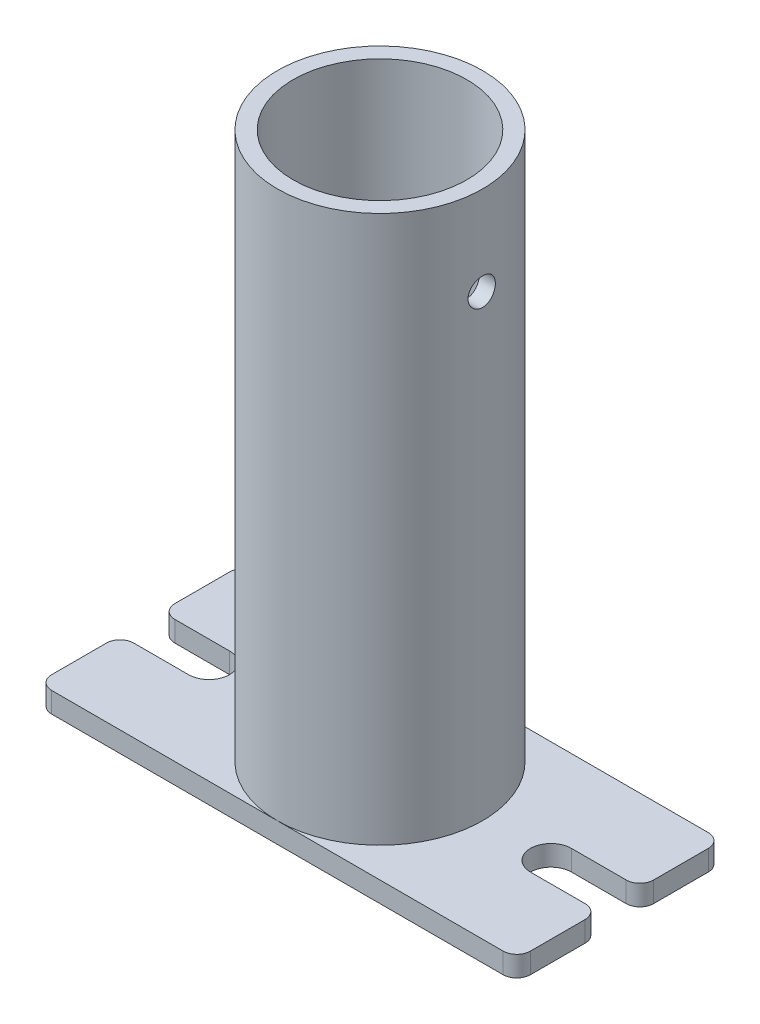
SolidWorks part; units mm, degrees
ref_plane "Front Plane" through (0, 0, 0) normal (0, 0, 1) x (1, 0, 0)
ref_plane "Top Plane" through (0, 0, 0) normal (0, 1, 0) x (1, 0, 0)
ref_plane "Right Plane" through (0, 0, 0) normal (1, 0, 0) x (0, 0, -1)
sketch "Sketch1" plane through (0, 0, 0) normal (0, 1, 0) x (1, 0, 0)
  line L0 (0, 15) -> (10, 15) construction
  line L1 (2, 0) -> (68, 0)
  line L2 (0, 2) -> (0, 10)
  line L3 (2, 30) -> (68, 30)
  line L4 (70, 2) -> (70, 10)
  line L5 (2, 18) -> (10, 18)
  line L6 (2, 12) -> (10, 12)
  line L7 (0, 20) -> (0, 28)
  line L8 (70, 15) -> (60, 15) construction
  line L9 (68, 12) -> (60, 12)
  line L10 (68, 18) -> (60, 18)
  line L11 (70, 20) -> (70, 28)
  arc A1 (10, 12) -> (10, 18) centre (10, 15) ccw
  arc A3 (60, 18) -> (60, 12) centre (60, 15) ccw
  arc A4 (68, 30) -> (70, 28) centre (68, 28) cw
  arc A5 (68, 18) -> (70, 20) centre (68, 20) ccw
  arc A6 (68, 12) -> (70, 10) centre (68, 10) cw
  arc A7 (68, 0) -> (70, 2) centre (68, 2) ccw
  arc A8 (2, 0) -> (0, 2) centre (2, 2) cw
  arc A9 (2, 12) -> (0, 10) centre (2, 10) ccw
  arc A10 (2, 18) -> (0, 20) centre (2, 20) cw
  arc A11 (0, 28) -> (2, 30) centre (2, 28) cw
  point P7 (5, 15)
  point P14 (65, 15)
  point P21 (70, 30)
  point P30 (0, 0)
  point P37 (0, 30)
  dimension "D3" = 2
  dimension "D1" = 30
  dimension "D2" = 70
extrude "Boss-Extrude2" add sketch "Sketch1" along normal blind 3
sketch "Sketch3" plane through (0, 3, 0) normal (0, 1, 0) x (1, 0, 0)
  line L0 (0, 10) -> (0, 2) construction
  circle A0 centre (35, 15) radius 15
  dimension "D1" = 35
extrude "Boss-Extrude3" add sketch "Sketch3" along normal blind 5
sketch "Sketch4" plane through (0, 8, 0) normal (0, 1, 0) x (1, 0, 0)
  circle A0 centre (35, 15) radius 12.7
  arc A1 (35, 0) -> (35, 30) centre (35, 15) ccw construction
  circle A2 centre (35, 15) radius 15
  dimension "D1" = 0
extrude "Boss-Extrude5" add sketch "Sketch4" along normal blind 75
sketch "Sketch5" plane through (70, 0, 0) normal (1, 0, 0) x (0, 0, -1)
  line L0 (30, 3) -> (30, 0) construction
  line L1 (2, 0) -> (10, 0) construction
  circle A0 centre (15, 70) radius 2
  dimension "D1" = 15
  dimension "D2" = 70
extrude "Cut-Extrude1" cut sketch "Sketch5" against normal blind 40
